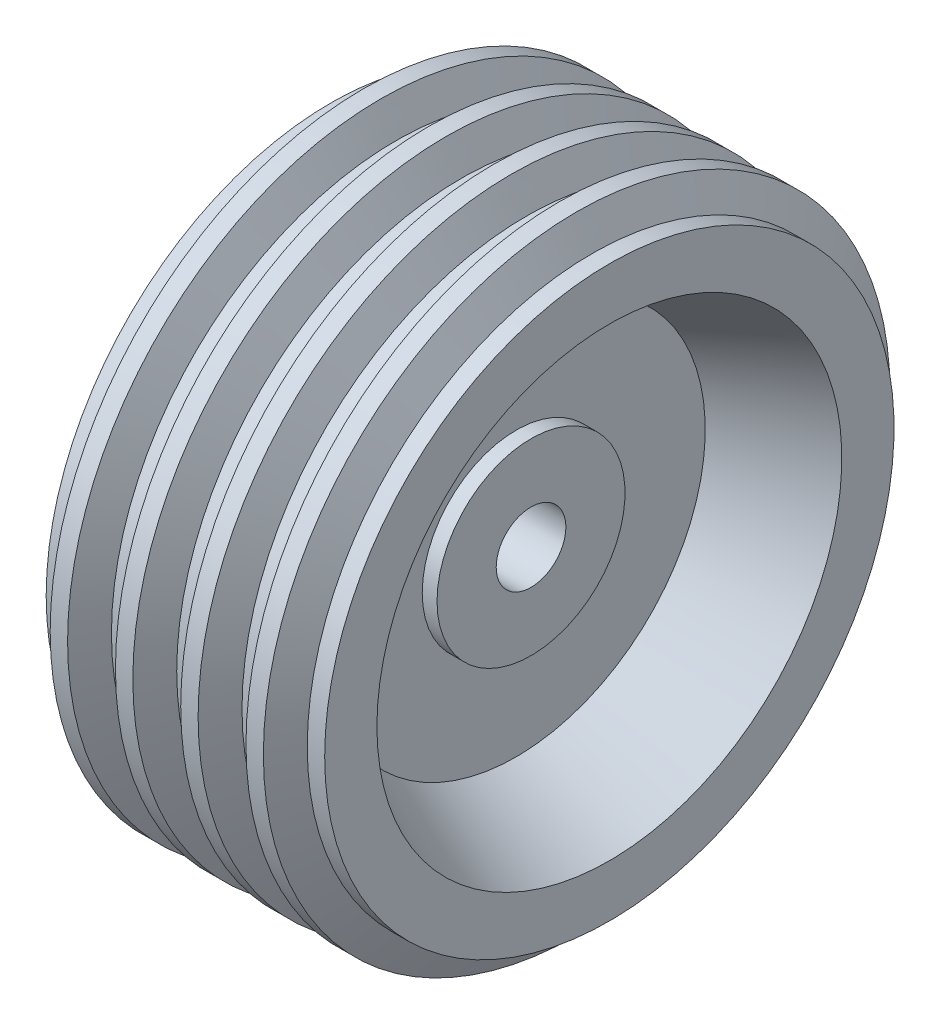
SolidWorks part; units mm, degrees
ref_plane "Front Plane" through (0, 0, 0) normal (0, 0, 1) x (1, 0, 0)
ref_plane "Top Plane" through (0, 0, 0) normal (0, 1, 0) x (1, 0, 0)
ref_plane "Right Plane" through (0, 0, 0) normal (1, 0, 0) x (0, 0, -1)
sketch "Sketch1" plane through (0, 0, 0) normal (0, 0, 1) x (1, 0, 0)
  line L0 (0, 0) -> (0, 20)
  line L1 (-35, 20) -> (35, 20)
  line L2 (35, 20) -> (35, 54)
  line L3 (35, 54) -> (26.5, 54)
  line L4 (26.5, 54) -> (26.5, 108.5962)
  line L6 (80, 163.5436) -> (80, 133.5436)
  line L7 (13.75, 180) -> (5, 163.5436)
  line L8 (13.75, 180) -> (23.75, 180)
  line L9 (5, 163.5436) -> (-5, 163.5436)
  line L10 (23.75, 180) -> (32.5, 163.5436)
  line L11 (-5, 163.5436) -> (5, 163.5436)
  line L12 (32.5, 163.5436) -> (42.5, 163.5436)
  line L13 (42.5, 163.5436) -> (51.2416, 180)
  line L14 (51.2416, 180) -> (61.2416, 180)
  line L15 (51.2416, 180) -> (61.2416, 180)
  line L16 (61.2416, 180) -> (69.9916, 163.5436)
  line L17 (32.5, 163.5436) -> (42.5, 163.5436)
  line L18 (69.9916, 163.5436) -> (80, 163.5436)
  line L19 (80, 133.5436) -> (26.5, 108.5962)
  line L20 (-80, 133.5436) -> (-26.5, 108.5962)
  line L21 (-69.9916, 163.5436) -> (-80, 163.5436)
  line L22 (-32.5, 163.5436) -> (-42.5, 163.5436)
  line L23 (-61.2416, 180) -> (-69.9916, 163.5436)
  line L24 (-51.2416, 180) -> (-61.2416, 180)
  line L27 (-51.2416, 180) -> (-61.2416, 180)
  line L28 (-42.5, 163.5436) -> (-51.2416, 180)
  line L30 (-32.5, 163.5436) -> (-42.5, 163.5436)
  line L32 (-23.75, 180) -> (-32.5, 163.5436)
  line L33 (-13.75, 180) -> (-23.75, 180)
  line L34 (-13.75, 180) -> (-5, 163.5436)
  line L35 (-80, 163.5436) -> (-80, 133.5436)
  line L36 (-26.5, 54) -> (-26.5, 108.5962)
  line L37 (-35, 54) -> (-26.5, 54)
  line L38 (-35, 20) -> (-35, 54)
  line L39 (-35, 0) -> (35, 0) construction
  point P29 (0, 163.5436)
  dimension "D1" = 20
  dimension "D2" = 5
  dimension "D3" = 13.75
  dimension "D4" = 54
  dimension "D5" = 108.5962
  dimension "D6" = 133.5436
  dimension "D7" = 163.5436
  dimension "D8" = 180
  dimension "D9" = 26.5
  dimension "D10" = 35
  dimension "D11" = 51.2416
  dimension "D12" = 80
revolve "Revolve2" add sketch "Sketch1" angle 360 about L39
